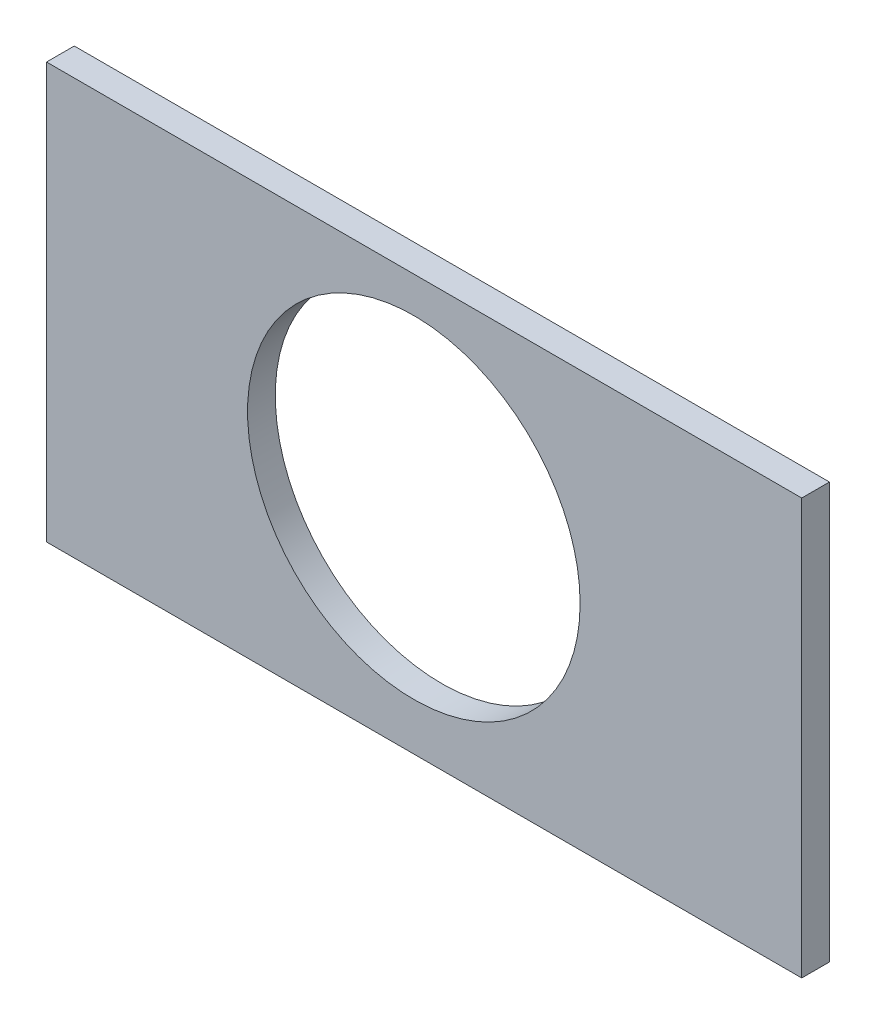
SolidWorks part; units mm, degrees
ref_plane "Front Plane" through (0, 0, 0) normal (0, 0, 1) x (1, 0, 0)
ref_plane "Top Plane" through (0, 0, 0) normal (0, 1, 0) x (1, 0, 0)
ref_plane "Right Plane" through (0, 0, 0) normal (1, 0, 0) x (0, 0, -1)
sketch "Sketch1" plane through (0, 0, 0) normal (0, 0, 1) x (1, 0, 0)
  line L1 (-27.25, -15) -> (27.25, -15)
  line L2 (-27.25, -15) -> (-27.25, 15)
  line L3 (-27.25, 15) -> (27.25, 15)
  line L4 (27.25, -15) -> (27.25, 15)
  line L5 (-27.25, -15) -> (27.25, 15) construction
  line L6 (-27.25, 15) -> (27.25, -15) construction
  circle A0 centre (-0.7438, 0.4094) radius 12
  point P0 (0, 0)
  dimension "D1" = 54.5
  dimension "D2" = 30
extrude "Boss-Extrude1" add sketch "Sketch1" along normal blind 2
